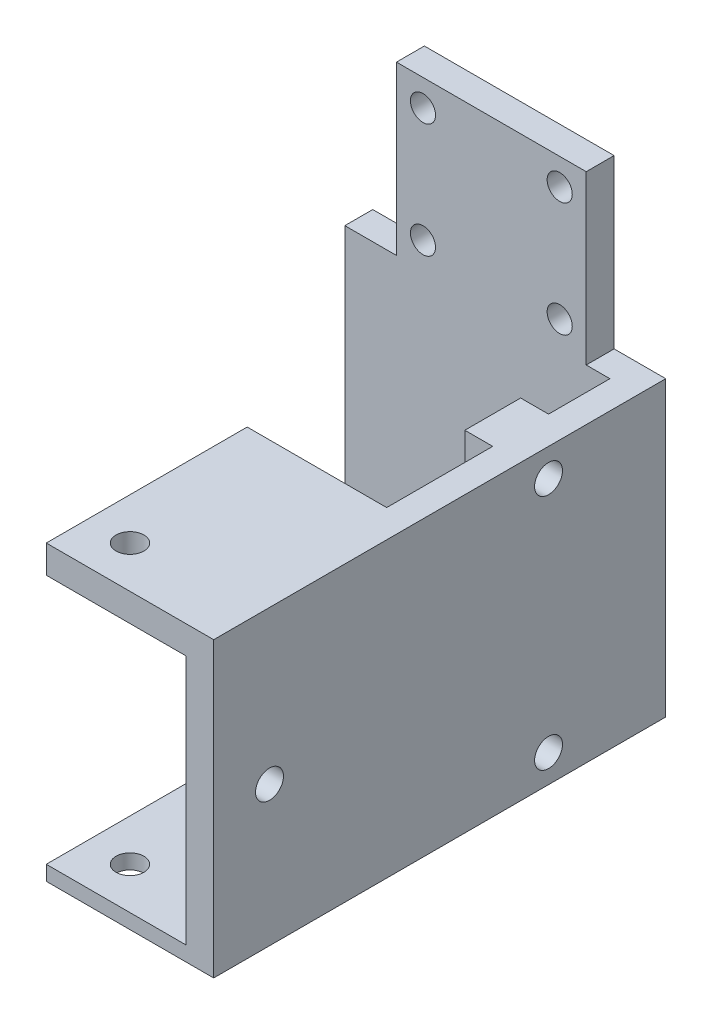
SolidWorks part; units mm, degrees
ref_plane "Front Plane" through (0, 0, 0) normal (0, 0, 1) x (1, 0, 0)
ref_plane "Top Plane" through (0, 0, 0) normal (0, 1, 0) x (1, 0, 0)
ref_plane "Right Plane" through (0, 0, 0) normal (1, 0, 0) x (0, 0, -1)
sketch "Sketch1" plane through (0, 0, 0) normal (0, 0, 1) x (1, 0, 0)
  line L0 (0, 30) -> (-9.25, 30)
  line L1 (0, 0) -> (34, 0)
  line L2 (0, 0) -> (0, 30)
  line L4 (34, 0) -> (34, 30)
  line L5 (-9.25, 30) -> (-9.25, 82.5)
  line L7 (43.25, 82.5) -> (43.25, 30)
  line L8 (34, 30) -> (43.25, 30)
  line L9 (0, 82.5) -> (-9.25, 82.5)
  line L11 (34, 82.5) -> (34, 112.5)
  line L12 (34, 112.5) -> (0, 112.5)
  line L13 (0, 82.5) -> (0, 112.5)
  line L14 (43.25, 82.5) -> (34, 82.5)
  circle A0 centre (4.75, 25.25) radius 2.25
  circle A1 centre (29.25, 25.25) radius 2.25
  circle A2 centre (29.25, 4.75) radius 2.25
  circle A3 centre (4.75, 4.75) radius 2.25
  circle A4 centre (4.75, 107.75) radius 2.25
  circle A5 centre (29.25, 107.75) radius 2.25
  circle A6 centre (29.25, 87.25) radius 2.25
  circle A7 centre (4.75, 87.25) radius 2.25
  dimension "D3" = 4.5
  dimension "D6" = 4.5
  dimension "D13" = 4.5
  dimension "D14" = 4.5
  dimension "D15" = 52.5
  dimension "D16" = 9.25
  dimension "D19" = 4.5
  dimension "D24" = 4.5
  dimension "D29" = 30
  dimension "D31" = 4.5
  dimension "D32" = 4.5
  dimension "D1" = 30
  dimension "D2" = 34
  dimension "D4" = 4.75
  dimension "D5" = 30
  dimension "D7" = 34
  dimension "D8" = 4.75
  dimension "D9" = 4.75
  dimension "D10" = 4.75
  dimension "D11" = 4.75
  dimension "D12" = 4.75
  dimension "D17" = 52.5
  dimension "D18" = 9.25
  dimension "D20" = 4.75
  dimension "D21" = 4.75
  dimension "D22" = 4.75
  dimension "D23" = 4.75
  dimension "D25" = 4.75
  dimension "D26" = 4.75
  dimension "D27" = 4.75
  dimension "D28" = 4.75
  dimension "D30" = 52.5
extrude "Boss-Extrude1" add sketch "Sketch1" along normal blind 5
sketch "Sketch2" plane through (0, 0, 5) normal (0, 0, 1) x (1, 0, 0)
  line L1 (-9.25, 82.5) -> (43.25, 82.5)
  line L2 (-9.25, 82.5) -> (-9.25, 30)
  line L3 (-9.25, 30) -> (43.25, 30)
  line L4 (43.25, 82.5) -> (43.25, 30)
  line L5 (-4.25, 77.5) -> (38.25, 77.5)
  line L6 (-4.25, 77.5) -> (-4.25, 35)
  line L7 (-4.25, 35) -> (38.25, 35)
  line L8 (38.25, 77.5) -> (38.25, 35)
  dimension "D1" = 5
  dimension "D2" = 5
  dimension "D3" = 5
  dimension "D4" = 5
extrude "Boss-Extrude2" add sketch "Sketch2" along normal blind 40
sketch "Sketch5" plane through (0, 0, 45) normal (0, 0, 1) x (1, 0, 0)
  line L0 (-9.25, 30) -> (43.25, 30) construction
  line L6 (43.25, 82.5) -> (-9.25, 82.5) construction
  line L7 (43.25, 82.5) -> (43.25, 30)
  line L8 (13.25, 82.5) -> (13.25, 77.5)
  line L9 (38.25, 77.5) -> (-4.25, 77.5) construction
  line L10 (13.25, 77.5) -> (38.25, 77.5)
  line L12 (0, 30) -> (34, 30) construction
  line L13 (13.25, 30) -> (13.25, 35)
  line L14 (-4.25, 35) -> (38.25, 35) construction
  line L15 (13.25, 35) -> (38.25, 35)
  line L16 (13.25, 82.5) -> (43.25, 82.5)
  line L17 (43.25, 30) -> (13.25, 30)
  line L18 (38.25, 77.5) -> (38.25, 35)
  dimension "D1" = 25
  dimension "D2" = 0
  dimension "D3" = 5
extrude "Boss-Extrude3" add sketch "Sketch5" along normal blind 36
sketch "Sketch6" plane through (0, 77.5, 0) normal (0, -1, 0) x (1, 0, 0)
  line L0 (13.25, 81) -> (13.25, 45) construction
  line L1 (13.25, 81) -> (38.25, 81) construction
  circle A0 centre (20.75, 73.5) radius 2.5
  dimension "D1" = 5
  dimension "D2" = 7.5
  dimension "D3" = 7.5
extrude "Cut-Extrude2" cut sketch "Sketch6" against normal through all both and the other way through all
sketch "Sketch7" plane through (43.25, 0, 0) normal (1, 0, 0) x (0, 0, -1)
  line L0 (-81, 30) -> (-81, 82.5) construction
  circle A0 centre (-71, 55.075) radius 2.5
  dimension "D1" = 5
  dimension "D2" = 10
  dimension "D3" = 27.425
extrude "Cut-Extrude3" cut sketch "Sketch7" against normal through all both
sketch "Sketch8" plane through (-9.25, 0, 0) normal (-1, 0, 0) x (0, 0, 1)
  line L0 (45, 82.5) -> (45, 30) construction
  line L1 (45, 74.5) -> (5, 74.5)
  line L2 (45, 74.5) -> (45, 38)
  line L3 (45, 38) -> (5, 38)
  line L4 (5, 74.5) -> (5, 38)
  line L6 (45, 30) -> (0, 30) construction
  line L7 (0, 82.5) -> (0, 30) construction
  line L8 (45, 82.5) -> (0, 82.5) construction
  dimension "D1" = 8
  dimension "D2" = 8
  dimension "D3" = 5
extrude "Cut-Extrude4" cut sketch "Sketch8" against normal blind 24
sketch "Sketch9" plane through (0, 35, 0) normal (0, 1, 0) x (1, 0, 0)
  line L0 (38.25, -81) -> (38.25, -5) construction
  line L1 (13.25, -81) -> (38.25, -81)
  line L2 (13.25, -81) -> (13.25, -55.4806)
  line L3 (13.25, -55.4806) -> (38.25, -55.4806)
  line L4 (38.25, -81) -> (38.25, -55.4806)
extrude "Cut-Extrude5" cut sketch "Sketch9" against normal blind 2.35
sketch "Sketch10" plane through (0, 0, 0) normal (-1, 0, 0) x (0, 0, 1)
  line L1 (0, 30) -> (5, 30)
  line L2 (0, 30) -> (0, 0)
  line L3 (0, 0) -> (5, 0)
  line L4 (5, 30) -> (5, 0)
extrude "Cut-Extrude6" cut sketch "Sketch10" against normal blind 119
sketch "Sketch11" plane through (-9.25, 0, 0) normal (-1, 0, 0) x (0, 0, 1)
  line L0 (45, 30) -> (0, 30) construction
  line L1 (45, 82.5) -> (5, 82.5)
  line L2 (45, 82.5) -> (45, 30)
  line L3 (45, 30) -> (5, 30)
  line L4 (5, 82.5) -> (5, 30)
  line L6 (0, 82.5) -> (0, 30) construction
  dimension "D1" = 5
extrude "Cut-Extrude7" cut sketch "Sketch11" against normal up to surface (47.5 mm away) up to face at (38.25, 52.575, 71)
sketch "Sketch12" plane through (38.25, 0, 0) normal (-1, 0, 0) x (0, 0, 1)
  line L1 (5, 82.5) -> (45, 82.5) construction
  line L4 (5, 30) -> (5, 82.5) construction
  circle A0 centre (21, 77.5) radius 2.5
  circle A1 centre (21, 35) radius 2.5
  dimension "D2" = 5
  dimension "D3" = 5
  dimension "D1" = 42.5
  dimension "D4" = 5
  dimension "D5" = 16
  dimension "D6" = 16
extrude "Cut-Extrude8" cut sketch "Sketch12" against normal blind 119
sketch "Sketch13" plane through (38.25, 0, 0) normal (-1, 0, 0) x (0, 0, 1)
  line L0 (5, 82.5) -> (45, 82.5) construction
  line L1 (16, 82.5) -> (26, 82.5)
  line L2 (16, 82.5) -> (16, 30)
  line L3 (16, 30) -> (26, 30)
  line L4 (26, 82.5) -> (26, 30)
  line L5 (45, 30) -> (5, 30) construction
  circle A0 centre (21, 77.5) radius 2.5
  circle A1 centre (21, 35) radius 2.5
  dimension "D3" = 5
  dimension "D4" = 5
  dimension "D1" = 5
  dimension "D2" = 5
extrude "Boss-Extrude4" add sketch "Sketch13" along normal blind 5
